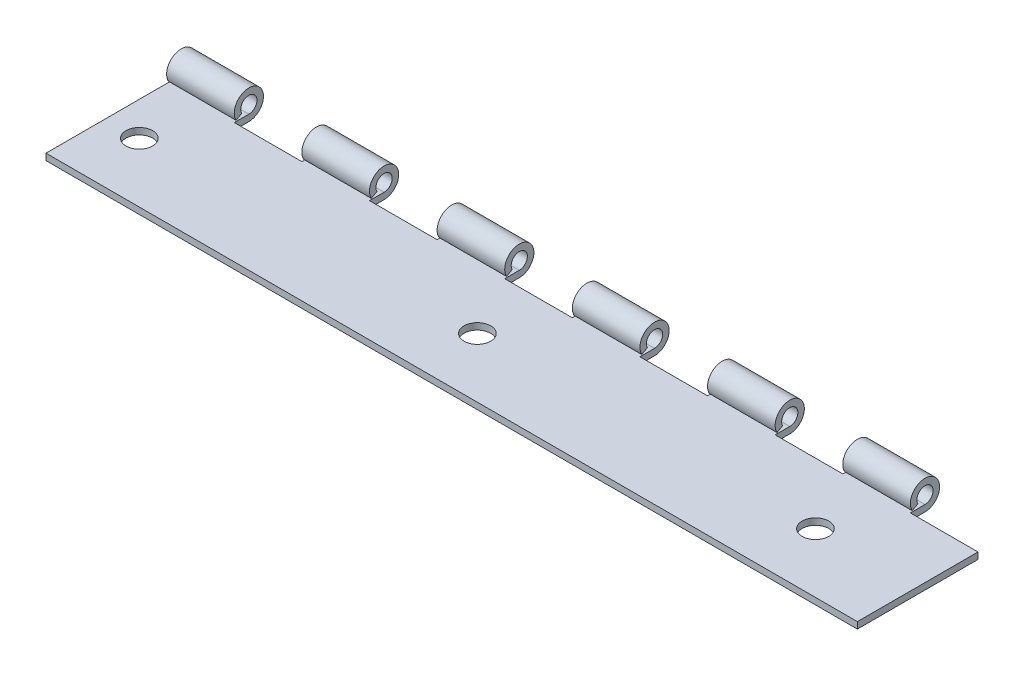
SolidWorks part; units mm, degrees
ref_plane "Front Plane" through (0, 0, 0) normal (0, 0, 1) x (1, 0, 0)
ref_plane "Top Plane" through (0, 0, 0) normal (0, 1, 0) x (1, 0, 0)
ref_plane "Right Plane" through (0, 0, 0) normal (1, 0, 0) x (0, 0, -1)
sketch "Sketch1" plane through (0, 0, 0) normal (0, 1, 0) x (1, 0, 0)
  line L0 (-76.2, 0) -> (76.2, 0) construction
  line L1 (-76.2, -25.4) -> (-76.2, 25.4) construction
  line L2 (-76.2, -25.4) -> (-69.85, -25.4) construction
  line L3 (-69.85, -25.4) -> (-6.35, -25.4) construction
  line L4 (-6.35, -25.4) -> (57.15, -25.4) construction
  line L5 (76.2, -25.4) -> (76.2, -14.224) construction
  line L6 (57.15, -25.4) -> (76.2, -25.4) construction
  line L7 (-76.2, 25.4) -> (-57.15, 25.4) construction
  line L8 (-57.15, 25.4) -> (6.35, 25.4) construction
  line L9 (6.35, 25.4) -> (69.85, 25.4) construction
  line L10 (69.85, 25.4) -> (76.2, 25.4) construction
  line L11 (57.15, -16.7259) -> (57.15, -11.7221) construction
  point P4 (0, 0)
  point P8 (-76.2, 0)
  point P17 (-63.5, 0)
  point P21 (57.15, -14.224)
  dimension "Leaf Height" = 152.4
  dimension "Overall Width" = 50.8
  dimension "Hole to End 1" = 6.35
  dimension "Hole Spacing" = 63.5
  dimension "D3" = 63.5
  dimension "Hole to End 2" = 19.05
  dimension "Hole Center to End" = 11.176
  dimension "D1" = 6.35
  dimension "D2" = 19.05
  dimension "D4" = 63.5
  dimension "D6" = 63.5
  dimension "Knuckle Length" = 12.7
  dimension "Hole Diameter" = 5.0038
sketch "Sketch2" plane through (0, 0, 0) normal (1, 0, 0) x (0, 0, -1)
  line L2 (0, -2.7432) -> (0, -1.524) construction
  line L4 (0, 1.524) -> (0, -1.524) construction
  point P8 (0, 0)
  dimension "Leaf Thickness" = 1.2192
  dimension "Pin Diameter" = 3.048
sketch "Sketch3" plane through (0, 0, 0) normal (1, 0, 0) x (0, 0, -1)
  line L3 (0, 0) -> (-2.7432, -1.524) construction
  line L4 (0, -2.7432) -> (-25.4, -2.7432)
  line L5 (-25.4, -2.7432) -> (-25.4, -1.524)
  line L7 (-25.4, -1.524) -> (0, -1.524)
  line L8 (-25.4, 0) -> (25.4, 0) construction
  line L9 (-1.3322, -0.7401) -> (-2.398, -1.3322)
  line L11 (-2.7432, 0) -> (-2.7432, -1.524) construction
  circle A4 centre (0, 0) radius 1.524 construction
  circle A5 centre (0, 0) radius 2.7432 construction
  arc A8 (-1.3322, -0.7401) -> (0, -1.524) centre (0, 0) cw
  arc A9 (-2.398, -1.3322) -> (0, -2.7432) centre (0, 0) cw
  point P0 (-2.398, -1.3322)
  point P13 (-1.3322, -0.7401)
extrude "Boss-Extrude1" add sketch "Sketch3" along normal mid plane 152.4
sketch "Sketch4" plane through (0, 0, 0) normal (0, 1, 0) x (1, 0, 0)
  line L0 (-76.2, -2.7432) -> (76.2, -2.7432) construction
  line L1 (-76.2, -2.7432) -> (76.2, -2.7432) construction
  line L2 (76.2, 2.7432) -> (-76.2, 2.7432) construction
  line L3 (76.2, 2.7432) -> (-76.2, 2.7432) construction
  line L4 (-63.5, -2.7432) -> (-63.5, 2.7432)
  line L6 (-63.5, 2.7432) -> (-50.8, 2.7432)
  line L7 (-50.8, -2.7432) -> (-63.5, -2.7432)
  line L8 (-50.8, 2.7432) -> (-50.8, -2.7432)
  point P8 (-63.5, 0)
  dimension "D1" = 12.7
extrude "Cut-Extrude1" cut sketch "Sketch4" against normal through all both and the other way through all
pattern_linear "LPattern1" count 6 spacing 25.4 along (1, 0, 0) of "Cut-Extrude1"
sketch "Sketch5" plane through (0, -1.524, 0) normal (0, 1, 0) x (1, 0, 0)
  line L0 (57.15, -14.224) -> (-69.85, -14.224) construction
  line L1 (-6.35, -14.224) -> (-6.35, -25.4) construction
  line L2 (-69.85, -14.224) -> (-69.85, -25.4) construction
  circle A0 centre (57.15, -14.224) radius 2.5019
  circle A1 centre (-6.35, -14.224) radius 2.5019
  circle A2 centre (-69.85, -14.224) radius 2.5019
extrude "Cut-Extrude2" cut sketch "Sketch5" against normal through all
equation "\"D3@Sketch1\"=\"Hole Spacing@Sketch1\""
equation "\"D1@Sketch1\"=\"Hole to End 1@Sketch1\""
equation "\"D2@Sketch1\"=\"Hole to End 2@Sketch1\""
equation "\"D4@Sketch1\"=\"Hole Spacing@Sketch1\""
equation "\"D6@Sketch1\"=\"D4@Sketch1\""
equation "\"D1@Boss-Extrude1\"=\"Leaf Height@Sketch1\""
equation "\"D1@Sketch4\"=\"Knuckle Length@Sketch1\""
equation "\"D3@LPattern1\"=\"Knuckle Length@Sketch1\"*2"
equation "\"D1@Sketch6\"=\"Pin Diameter@Sketch2\""
equation "\"D1@Boss-Extrude2\"=\"Leaf Height@Sketch1\""
equation "\"D1@Sketch7\"=\"Pin Diameter@Sketch2\""
equation "\"D2@Sketch7\"=\"Overall Width@Sketch1\""
equation "\"D3@Sketch7\"=\"Leaf Thickness@Sketch2\""
